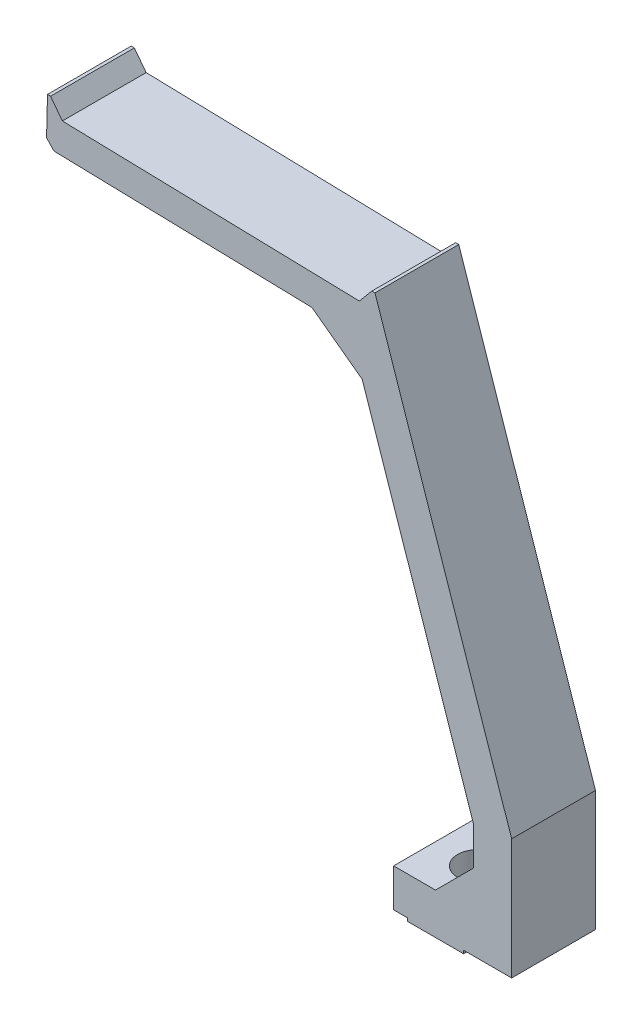
SolidWorks part; units mm, degrees
ref_plane "Спереди" through (0, 0, 0) normal (0, 0, 1) x (1, 0, 0)
ref_plane "Сверху" through (0, 0, 0) normal (0, 1, 0) x (1, 0, 0)
ref_plane "Справа" through (0, 0, 0) normal (1, 0, 0) x (0, 0, -1)
sketch "Эскиз1" plane through (0, 0, 0) normal (0, 0, 1) x (1, 0, 0)
  line L0 (-5.5, 0.4) -> (-3.7, 0.4)
  line L10 (-3.7, 0.4) -> (-3.7, 0)
  line L11 (-3.7, 0) -> (3.7, 0)
  line L12 (3.7, 0) -> (3.7, 0.4)
  line L13 (0, 0) -> (0, 23.4909) construction
  line L14 (3.7, 0.4) -> (10, 0.4)
  line L15 (10, 0.4) -> (10, 16.2223)
  line L18 (-11.2272, 63.4) -> (-51.0874, 64.4)
  line L19 (-51.0874, 64.4) -> (-50.9369, 70.3981)
  line L23 (10, -29.9135) -> (10, -50029.9135) construction
  line L24 (-10, -23.8573) -> (-10, -50023.8573) construction
  line L25 (-2.5, -31.6658) -> (-2.5, -50031.6658) construction
  line L26 (-5.5, 0.4) -> (-5.5, 5.4)
  line L27 (-6.5, -3.3619) -> (-6.5, -50003.3619) construction
  line L28 (-5.5, 5.4) -> (5, 5.4)
  line L29 (5, 5.4) -> (5, 15.4)
  line L30 (5, 15.4) -> (-11.2272, 63.4)
  line L31 (10, 16.2223) -> (-7.9505, 69.3197)
  line L32 (0, 25.4) -> (-10, 25.4) construction
  line L34 (-10, 67.3705) -> (-48.9877, 68.3486)
  line L36 (-7.9505, 69.3197) -> (-8.3503, 69.3297)
  line L37 (-8.3503, 69.3297) -> (-10, 67.3705)
  line L38 (-50.9369, 70.3981) -> (-50.5371, 70.3881)
  line L39 (-50.5371, 70.3881) -> (-48.9877, 68.3486)
  line L40 (-10, 67.3705) -> (-10.1003, 63.3717) construction
  line L41 (-48.9877, 68.3486) -> (-49.0881, 64.3498) construction
  point P21 (0, 0)
  dimension "D3" = 1
  dimension "D4" = 16.5
  dimension "D5" = 63
  dimension "D6" = 1
  dimension "D7" = 0.4
  dimension "D8" = 0.4
  dimension "D9" = 7.4
  dimension "D10" = 0.4
  dimension "D11" = 5
  dimension "D12" = 5
  dimension "D13" = 10
  dimension "D14" = 20
  dimension "D15" = 12.5
  dimension "D16" = 10
  dimension "D17" = 5.5
  dimension "D18" = 15
  dimension "D19" = 5
  dimension "D20" = 25
  dimension "D21" = 2
  dimension "D22" = 6
  dimension "D23" = 39
  dimension "D24" = 2
  dimension "D25" = 4
  dimension "D26" = 2
  dimension "D27" = 91.437
extrude "Бобышка-Вытянуть1" add sketch "Эскиз1" along normal blind 11
ref_plane "Плоскость1" through (0, 67.4, 0) normal (0, -1, 0) x (-1, 0, 0)
chamfer "Фаска2" distance 5 2 edges at (5, 5.4, 5.5) (-11.2272, 63.4, 5.5)
chamfer "Фаска3" distance 1 angle 45 1 edges at (-51.0874, 64.4, 5.5)
sketch "Эскиз2" plane through (0, 5.4, 0) normal (0, 1, 0) x (1, 0, 0)
  line L2 (0, 0) -> (0, -11) construction
  line L3 (0, -11) -> (-5.5, -11) construction
  circle A0 centre (0, -5.5) radius 2.6
  point P7 (0, -5.5)
  dimension "D1" = 5.2
extrude "Вырез-Вытянуть1" cut sketch "Эскиз2" against normal through all
sketch "Эскиз3" plane through (0, 5.4, 0) normal (0, 1, 0) x (1, 0, 0)
  circle A0 centre (0, -5.5) radius 5
  dimension "D1" = 10
extrude "Вырез-Вытянуть2" cut sketch "Эскиз3" along normal blind 5
